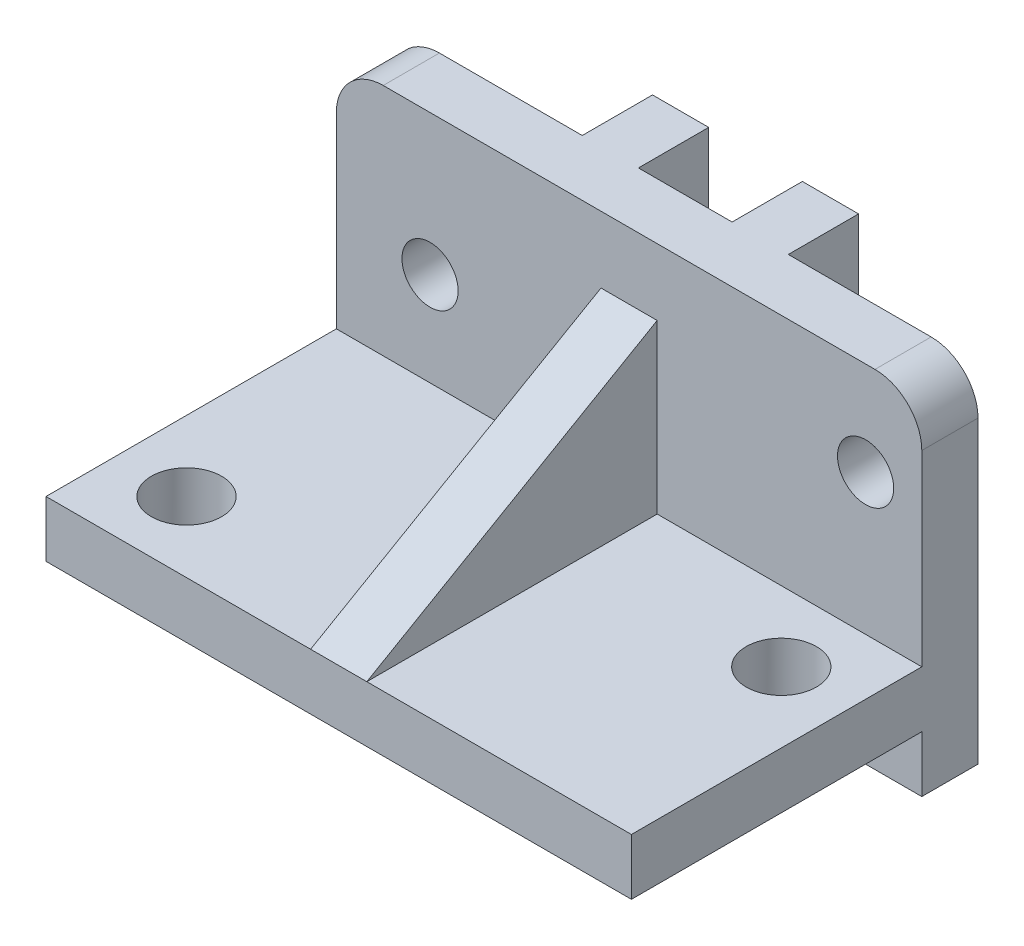
SolidWorks part; units mm, degrees
ref_plane "Front Plane" through (0, 0, 0) normal (0, 0, 1) x (1, 0, 0)
ref_plane "Top Plane" through (0, 0, 0) normal (0, 1, 0) x (1, 0, 0)
ref_plane "Right Plane" through (0, 0, 0) normal (1, 0, 0) x (0, 0, -1)
sketch "Sketch1" plane through (0, 0, 0) normal (1, 0, 0) x (0, 0, -1)
  line L0 (0, 0) -> (62, 0)
  line L1 (62, 0) -> (62, -12)
  line L2 (62, -12) -> (74, -12)
  line L3 (74, -12) -> (74, 62)
  line L4 (74, 62) -> (62, 62)
  line L5 (62, 62) -> (62, 12)
  line L6 (62, 12) -> (0, 12)
  line L7 (0, 12) -> (0, 0)
  point P3 (62, -6)
  dimension "D1" = 12
  dimension "D2" = 62
  dimension "D3" = 12
  dimension "D4" = 62
  dimension "D5" = 12
extrude "Boss-Extrude1" add sketch "Sketch1" against normal blind 125
fillet "Fillet1" radius 10 2 edges at (-125, 62, -68) (0, 62, -68)
ref_plane "Plane1" through (0, 62, 0) normal (0, -1, 0) x (-1, 0, 0)
sketch "Sketch2" plane through (0, 62, 0) normal (0, -1, 0) x (-1, 0, 0)
  line L0 (72.5, 74) -> (72.5, 89)
  line L1 (125, 74) -> (0, 74) construction
  line L2 (62.5, 74) -> (62.5, 67.754) construction
  line L3 (72.5, 89) -> (84.5, 89)
  line L4 (84.5, 89) -> (84.5, 74)
  line L5 (40.5, 89) -> (40.5, 74)
  line L6 (52.5, 74) -> (52.5, 89)
  line L7 (52.5, 89) -> (40.5, 89)
  line L8 (84.5, 74) -> (72.5, 74)
  line L9 (52.5, 74) -> (40.5, 74)
  dimension "D1" = 15
  dimension "D2" = 12
  dimension "D3" = 10
extrude "Boss-Extrude2" add sketch "Sketch2" along normal blind 74
sketch "Sketch3" plane through (0, 12, 0) normal (0, 1, 0) x (1, 0, 0)
  line L0 (-125, 62) -> (-125, 0) construction
  line L3 (-125, 0) -> (0, 0) construction
  line L4 (0, 62) -> (0, 0) construction
  line L5 (-125, 62) -> (0, 62) construction
  circle A0 centre (-110, 15) radius 7.5
  circle A1 centre (-15, 47) radius 7.5
  dimension "D1" = 15
  dimension "D4" = 15
  dimension "D2" = 15
  dimension "D3" = 15
  dimension "D5" = 15
  dimension "D6" = 15
extrude "Cut-Extrude1" cut sketch "Sketch3" against normal through all
sketch "Sketch4" plane through (0, 0, -62) normal (0, 0, 1) x (1, 0, 0)
  line L0 (-125, 52) -> (-125, 12) construction
  line L1 (-115, 62) -> (-10, 62) construction
  line L2 (0, 52) -> (0, 12) construction
  line L3 (-125, 12) -> (0, 12) construction
  circle A0 centre (-12, 42) radius 6
  circle A1 centre (-105, 32) radius 6
  point P12 (-8.769, 46.7587)
  dimension "D1" = 12
  dimension "D2" = 20
  dimension "D3" = 30
  dimension "D4" = 12
  dimension "D5" = 30
extrude "Cut-Extrude2" cut sketch "Sketch4" against normal through all
ref_plane "Plane2" through (-62.5, 0, 0) normal (1, 0, 0) x (0, 0, -1)
sketch "Sketch5" plane through (-62.5, 0, 0) normal (1, 0, 0) x (0, 0, -1)
  line L0 (0, 12) -> (62, 12)
  line L1 (0, 12) -> (62, 47.7957)
  line L2 (62, 52) -> (62, 12) construction
  line L3 (62, 47.7957) -> (62, 12)
  dimension "D1" = 30
extrude "Boss-Extrude3" add sketch "Sketch5" along normal mid plane 12
